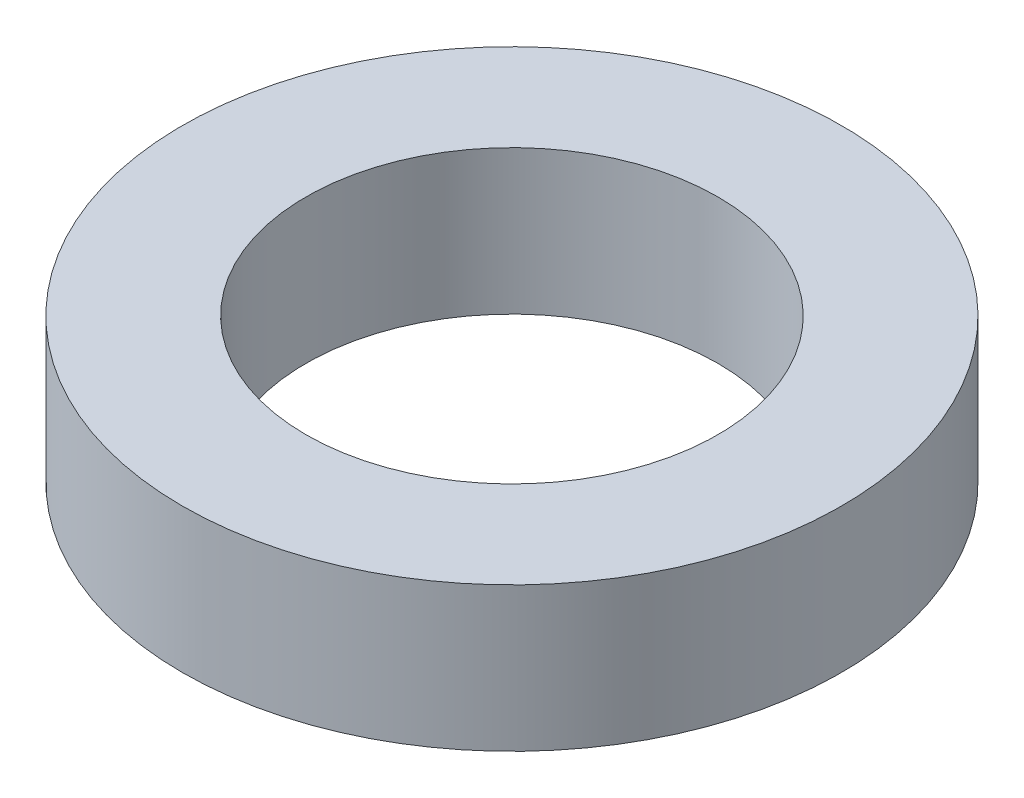
SolidWorks part; units mm, degrees
ref_plane "前视基准面" through (0, 0, 0) normal (0, 0, 1) x (1, 0, 0)
ref_plane "上视基准面" through (0, 0, 0) normal (0, 1, 0) x (1, 0, 0)
ref_plane "右视基准面" through (0, 0, 0) normal (1, 0, 0) x (0, 0, -1)
sketch "草图1" plane through (0, 0, 0) normal (0, 1, 0) x (1, 0, 0)
  circle A0 centre (0, 0) radius 10
  circle A1 centre (0, 0) radius 16
  dimension "D1" = 32
  dimension "D2" = 20
extrude "凸台-拉伸1" add sketch "草图1" along normal blind 7
